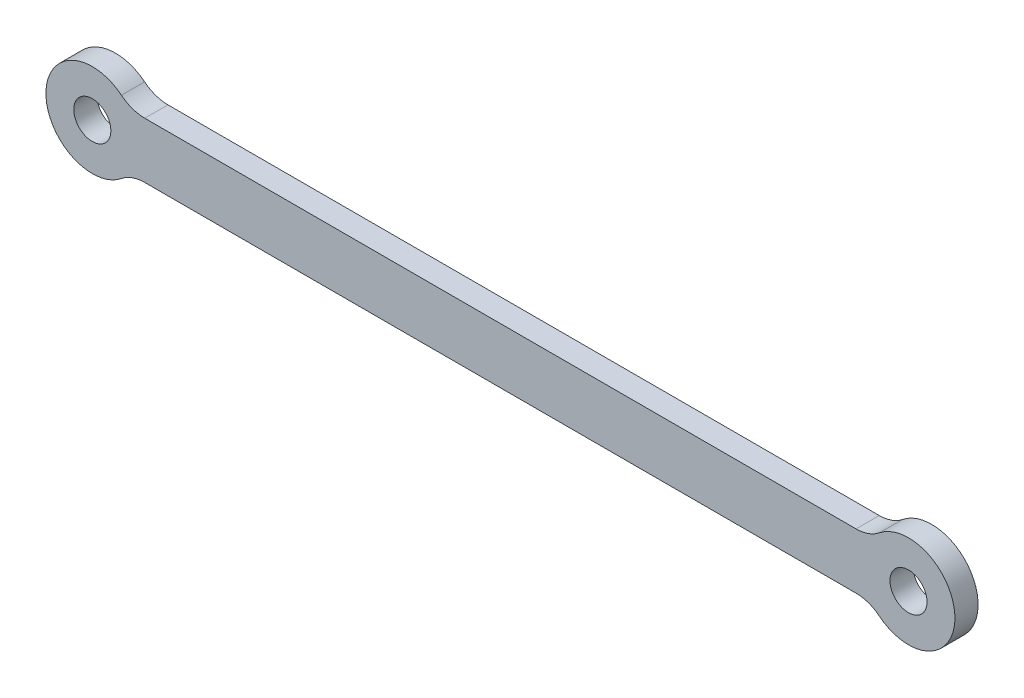
SolidWorks part; units mm, degrees
material "Thornel Mat VMA"
ref_plane "前视基准面" through (0, 0, 0) normal (0, 0, 1) x (1, 0, 0)
ref_plane "上视基准面" through (0, 0, 0) normal (0, 1, 0) x (1, 0, 0)
ref_plane "右视基准面" through (0, 0, 0) normal (1, 0, 0) x (0, 0, -1)
sketch "草图1" plane through (0, 0, 0) normal (0, 0, 1) x (1, 0, 0)
  line L0 (-88, 0) -> (88, 0) construction
  line L1 (-88, 0) -> (88, 0) construction
  line L2 (-88, 6) -> (88, 6)
  line L3 (-88, -6) -> (88, -6)
  circle A0 centre (88, 0) radius 2.1
  circle A1 centre (-88, 0) radius 2.1
  arc A2 (-88, 6) -> (-88, -6) centre (-88, 0) ccw
  arc A3 (88, -6) -> (88, 6) centre (88, 0) ccw
  point P4 (0, 0)
  point P7 (0, 0)
  dimension "D2" = 4.2
  dimension "D3" = 6
  dimension "D1" = 176
extrude "凸台-拉伸1" add sketch "草图1" along normal blind 5
sketch "草图2" plane through (0, 0, 5) normal (0, 0, 1) x (1, 0, 0)
  circle A0 centre (-88, 0) radius 10
  circle A1 centre (88, 0) radius 10
  circle A2 centre (-88, 0) radius 4 construction
  circle A3 centre (88, 0) radius 4 construction
  dimension "D1" = 8
  dimension "D2" = 20
extrude "凸台-拉伸2" add sketch "草图2" against normal blind 5
sketch "草图3" plane through (0, 0, 5) normal (0, 0, 1) x (1, 0, 0)
  circle A0 centre (-88, 0) radius 4
  circle A1 centre (88, 0) radius 4
  dimension "D1" = 8
extrude "切除-拉伸1" cut sketch "草图3" against normal blind 5
fillet "圆角1" radius 8 4 edges at (-80, 6, 2.5) (80, 6, 2.5) (80, -6, 2.5) (-80, -6, 2.5)
